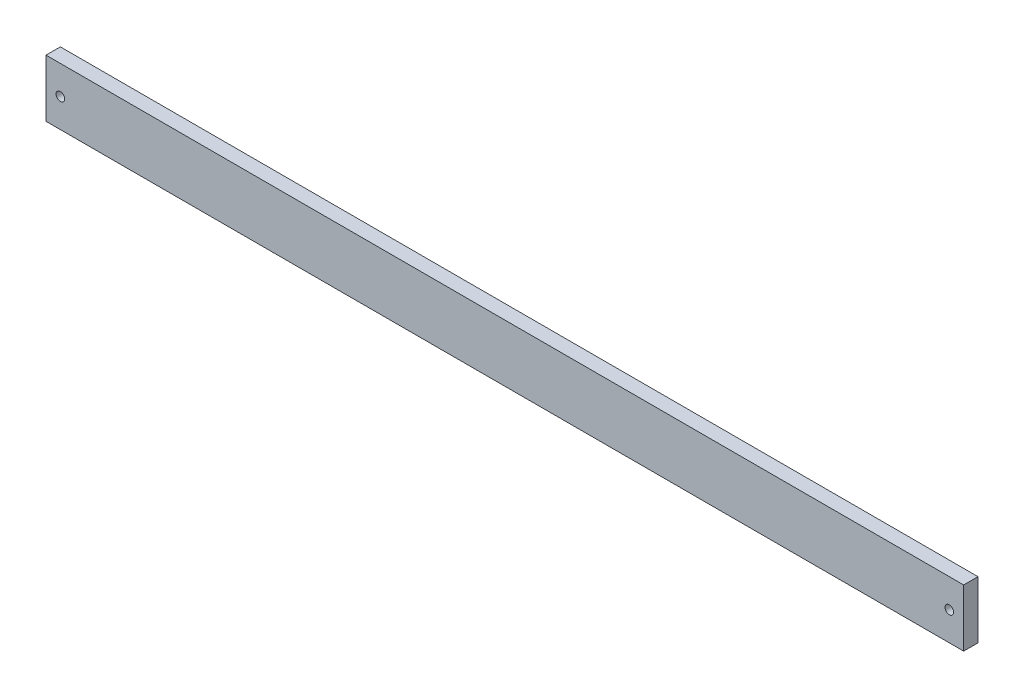
SolidWorks part; units mm, degrees
ref_plane "Front Plane" through (0, 0, 0) normal (0, 0, 1) x (1, 0, 0)
ref_plane "Top Plane" through (0, 0, 0) normal (0, 1, 0) x (1, 0, 0)
ref_plane "Right Plane" through (0, 0, 0) normal (1, 0, 0) x (0, 0, -1)
sketch "Sketch1" plane through (0, 0, 0) normal (0, 0, 1) x (1, 0, 0)
  line L1 (160, -10) -> (-160, -10)
  line L2 (160, -10) -> (160, 10)
  line L3 (160, 10) -> (-160, 10)
  line L4 (-160, -10) -> (-160, 10)
  line L5 (160, -10) -> (-160, 10) construction
  line L6 (160, 10) -> (-160, -10) construction
  point P0 (0, 0)
  dimension "D1" = 20
  dimension "D2" = 320
extrude "Boss-Extrude1" add sketch "Sketch1" along normal blind 5
sketch "Sketch2" plane through (0, 0, 5) normal (0, 0, 1) x (1, 0, 0)
  line L0 (-160, 0) -> (160, 0) construction
  line L1 (-160, 10) -> (-160, -10) construction
  line L2 (160, -10) -> (160, 10) construction
  line L3 (0, 0) -> (0, 10) construction
  line L4 (160, 10) -> (-160, 10) construction
  circle A0 centre (-155, 0) radius 1.5
  circle A1 centre (155, 0) radius 1.5
  dimension "D1" = 3
  dimension "D2" = 155
extrude "Cut-Extrude1" cut sketch "Sketch2" against normal through all
